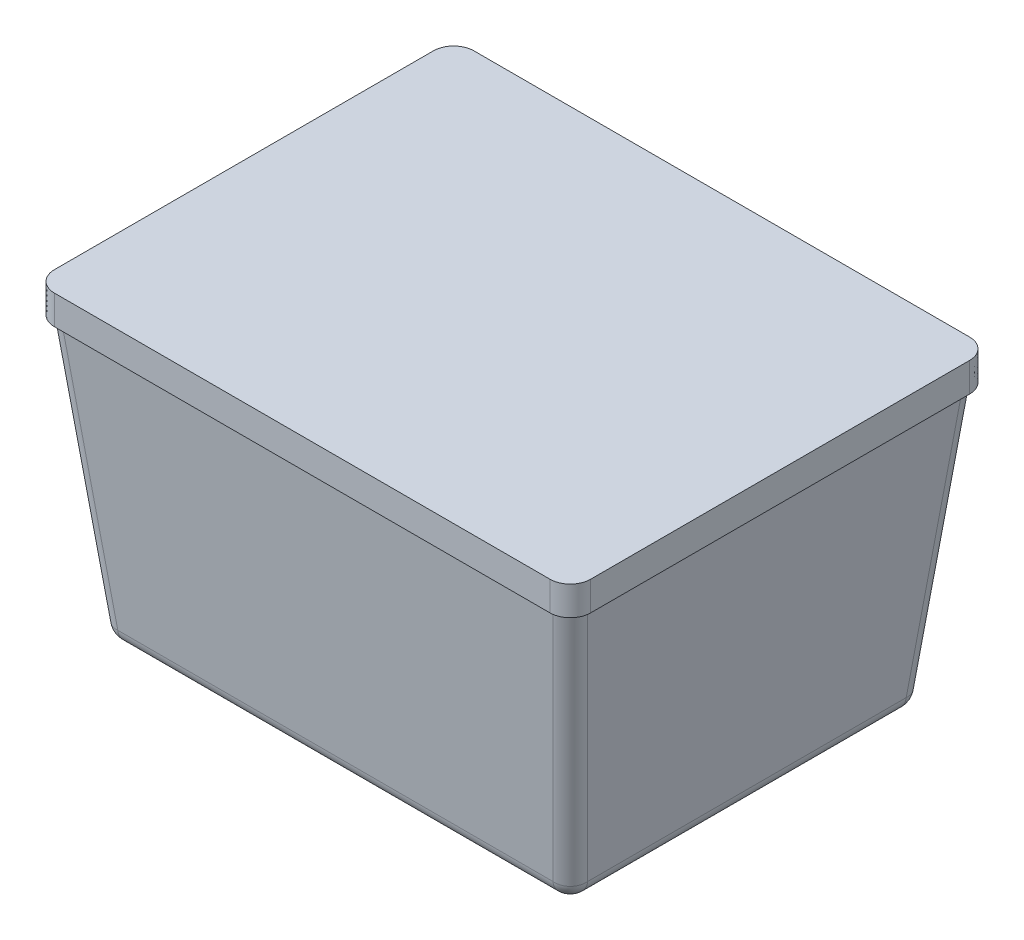
SolidWorks part; units mm, degrees
ref_plane "Alzado" through (0, 0, 0) normal (0, 0, 1) x (1, 0, 0)
ref_plane "Planta" through (0, 0, 0) normal (0, 1, 0) x (1, 0, 0)
ref_plane "Vista lateral" through (0, 0, 0) normal (1, 0, 0) x (0, 0, -1)
sketch "Croquis1" plane through (0, 0, 0) normal (0, 1, 0) x (1, 0, 0)
  line L1 (400, -300) -> (-400, -300)
  line L2 (400, -300) -> (400, 300)
  line L3 (400, 300) -> (-400, 300)
  line L4 (-400, -300) -> (-400, 300)
  line L5 (400, -300) -> (-400, 300) construction
  line L6 (400, 300) -> (-400, -300) construction
  point P0 (0, 0)
  dimension "D1" = 600
  dimension "D2" = 800
extrude "Extruir1" add sketch "Croquis1" along normal blind 520 draft 6 draft outward yes
fillet "Redondeo1" radius 30 8 edges at (0, 0, 300) (400, 0, 0) (0, 0, -300) (-400, 0, 0) (-427.3271, 260, -327.3271) (427.3271, 260, -327.3271) (427.3271, 260, 327.3271) (-427.3271, 260, 327.3271)
shell "Vaciado1" thickness 10
sketch "Croquis2" plane through (0, 520, 0) normal (0, 1, 0) x (1, 0, 0)
  line L24 (424.8185, 359.6542) -> (-424.8185, 359.6542)
  line L25 (459.6542, -324.8185) -> (459.6542, 324.8185)
  line L26 (-424.8185, -359.6542) -> (424.8185, -359.6542)
  line L27 (-459.6542, 324.8185) -> (-459.6542, -324.8185)
  line L28 (424.8185, 359.6542) -> (-424.8185, 359.6542)
  line L29 (459.6542, -324.8185) -> (459.6542, 324.8185)
  line L30 (-424.8185, -359.6542) -> (424.8185, -359.6542)
  line L31 (-459.6542, 324.8185) -> (-459.6542, -324.8185)
  spline S0 degree 3 poles (663.0928, -3479.8397) (-47.6648, -298.1304) (-303.9531, 384.1635) (-432.7137, 358.7732) (-433.8149, 358.5002) (-435.4515, 358.0079) (-435.9946, 357.83) (-437.0755, 357.446) (-437.6138, 357.2397) (-440.2615, 356.1489) (-442.2653, 355.0812) (-445.1032, 353.1931) (-446.0209, 352.5157) (-447.3539, 351.425) (-447.7906, 351.0493) (-448.6395, 350.2812) (-449.053, 349.888) (-451.067, 347.8765) (-452.5079, 346.1233) (-454.4118, 343.2761) (-455.0058, 342.2851) (-456.0832, 340.2672) (-456.5688, 339.238) (-457.8704, 336.0912) (-458.5327, 333.9145) (-496.2815, 144.0654) (1020.3325, -196.8187) (3414.6325, -624.2857) knots -7.056418 -7.056418 -7.056418 -7.056418 0.125 0.125 0.1875 0.1875 0.21875 0.21875 0.25 0.25 0.375 0.375 0.4375 0.4375 0.46875 0.46875 0.5 0.5 0.625 0.625 0.6875 0.6875 0.75 0.75 0.875 0.875 11.262721 11.262721 11.262721 11.262721 only from (-424.8185, 359.6542) to (-459.6542, 324.8185)
  spline S1 degree 3 poles (-3379.8397, -763.0928) (-198.1304, -52.3352) (484.1635, 203.9531) (458.7732, 332.7137) (458.5002, 333.8149) (458.0079, 335.4515) (457.83, 335.9946) (457.446, 337.0755) (457.2397, 337.6138) (456.1489, 340.2615) (455.0812, 342.2653) (453.1931, 345.1032) (452.5157, 346.0209) (451.425, 347.3539) (451.0493, 347.7906) (450.2812, 348.6395) (449.888, 349.053) (447.8765, 351.067) (446.1233, 352.5079) (443.2761, 354.4118) (442.2851, 355.0058) (440.2672, 356.0832) (439.238, 356.5688) (436.0912, 357.8704) (433.9145, 358.5327) (244.0654, 396.2815) (-96.8187, -1120.3325) (-524.2857, -3514.6325) knots -7.056418 -7.056418 -7.056418 -7.056418 0.125 0.125 0.1875 0.1875 0.21875 0.21875 0.25 0.25 0.375 0.375 0.4375 0.4375 0.46875 0.46875 0.5 0.5 0.625 0.625 0.6875 0.6875 0.75 0.75 0.875 0.875 11.262721 11.262721 11.262721 11.262721 only from (459.6542, 324.8185) to (424.8185, 359.6542)
  spline S2 degree 3 poles (-663.0928, 3479.8397) (47.6648, 298.1304) (303.9531, -384.1635) (432.7137, -358.7732) (433.8149, -358.5002) (435.4515, -358.0079) (435.9946, -357.83) (437.0755, -357.446) (437.6138, -357.2397) (440.2615, -356.1489) (442.2653, -355.0812) (445.1032, -353.1931) (446.0209, -352.5157) (447.3539, -351.425) (447.7906, -351.0493) (448.6395, -350.2812) (449.053, -349.888) (451.067, -347.8765) (452.5079, -346.1233) (454.4118, -343.2761) (455.0058, -342.2851) (456.0832, -340.2672) (456.5688, -339.238) (457.8704, -336.0912) (458.5327, -333.9145) (496.2815, -144.0654) (-1020.3325, 196.8187) (-3414.6325, 624.2857) knots -7.056418 -7.056418 -7.056418 -7.056418 0.125 0.125 0.1875 0.1875 0.21875 0.21875 0.25 0.25 0.375 0.375 0.4375 0.4375 0.46875 0.46875 0.5 0.5 0.625 0.625 0.6875 0.6875 0.75 0.75 0.875 0.875 11.262721 11.262721 11.262721 11.262721 only from (424.8185, -359.6542) to (459.6542, -324.8185)
  spline S3 degree 3 poles (3379.8397, 763.0928) (198.1304, 52.3352) (-484.1635, -203.9531) (-458.7732, -332.7137) (-458.5002, -333.8149) (-458.0079, -335.4515) (-457.83, -335.9946) (-457.446, -337.0755) (-457.2397, -337.6138) (-456.1489, -340.2615) (-455.0812, -342.2653) (-453.1931, -345.1032) (-452.5157, -346.0209) (-451.425, -347.3539) (-451.0493, -347.7906) (-450.2812, -348.6395) (-449.888, -349.053) (-447.8765, -351.067) (-446.1233, -352.5079) (-443.2761, -354.4118) (-442.2851, -355.0058) (-440.2672, -356.0832) (-439.238, -356.5688) (-436.0912, -357.8704) (-433.9145, -358.5327) (-244.0654, -396.2815) (96.8187, 1120.3325) (524.2857, 3514.6325) knots -7.056418 -7.056418 -7.056418 -7.056418 0.125 0.125 0.1875 0.1875 0.21875 0.21875 0.25 0.25 0.375 0.375 0.4375 0.4375 0.46875 0.46875 0.5 0.5 0.625 0.625 0.6875 0.6875 0.75 0.75 0.875 0.875 11.262721 11.262721 11.262721 11.262721 only from (-459.6542, -324.8185) to (-424.8185, -359.6542)
  spline S4 degree 3 poles (-424.8185, 359.6542) (-427.1201, 359.6542) (-429.3809, 359.4304) (-432.7137, 358.7732) (-433.8149, 358.5002) (-435.4515, 358.0079) (-435.9946, 357.83) (-437.0755, 357.446) (-437.6138, 357.2397) (-440.2615, 356.1489) (-442.2653, 355.0812) (-445.1032, 353.1931) (-446.0209, 352.5157) (-447.3539, 351.425) (-447.7906, 351.0493) (-448.6395, 350.2812) (-449.053, 349.888) (-451.067, 347.8765) (-452.5079, 346.1233) (-454.4118, 343.2761) (-455.0058, 342.2851) (-456.0832, 340.2672) (-456.5688, 339.238) (-457.8704, 336.0912) (-458.5327, 333.9145) (-459.4304, 329.3998) (-459.6542, 327.1202) (-459.6542, 324.8185) knots 0 0 0 0 0.125 0.125 0.1875 0.1875 0.21875 0.21875 0.25 0.25 0.375 0.375 0.4375 0.4375 0.46875 0.46875 0.5 0.5 0.625 0.625 0.6875 0.6875 0.75 0.75 0.875 0.875 1 1 1 1
  spline S5 degree 3 poles (459.6542, 324.8185) (459.6542, 327.1201) (459.4304, 329.3809) (458.7732, 332.7137) (458.5002, 333.8149) (458.0079, 335.4515) (457.83, 335.9946) (457.446, 337.0755) (457.2397, 337.6138) (456.1489, 340.2615) (455.0812, 342.2653) (453.1931, 345.1032) (452.5157, 346.0209) (451.425, 347.3539) (451.0493, 347.7906) (450.2812, 348.6395) (449.888, 349.053) (447.8765, 351.067) (446.1233, 352.5079) (443.2761, 354.4118) (442.2851, 355.0058) (440.2672, 356.0832) (439.238, 356.5688) (436.0912, 357.8704) (433.9145, 358.5327) (429.3998, 359.4304) (427.1202, 359.6542) (424.8185, 359.6542) knots 0 0 0 0 0.125 0.125 0.1875 0.1875 0.21875 0.21875 0.25 0.25 0.375 0.375 0.4375 0.4375 0.46875 0.46875 0.5 0.5 0.625 0.625 0.6875 0.6875 0.75 0.75 0.875 0.875 1 1 1 1
  spline S6 degree 3 poles (424.8185, -359.6542) (427.1201, -359.6542) (429.3809, -359.4304) (432.7137, -358.7732) (433.8149, -358.5002) (435.4515, -358.0079) (435.9946, -357.83) (437.0755, -357.446) (437.6138, -357.2397) (440.2615, -356.1489) (442.2653, -355.0812) (445.1032, -353.1931) (446.0209, -352.5157) (447.3539, -351.425) (447.7906, -351.0493) (448.6395, -350.2812) (449.053, -349.888) (451.067, -347.8765) (452.5079, -346.1233) (454.4118, -343.2761) (455.0058, -342.2851) (456.0832, -340.2672) (456.5688, -339.238) (457.8704, -336.0912) (458.5327, -333.9145) (459.4304, -329.3998) (459.6542, -327.1202) (459.6542, -324.8185) knots 0 0 0 0 0.125 0.125 0.1875 0.1875 0.21875 0.21875 0.25 0.25 0.375 0.375 0.4375 0.4375 0.46875 0.46875 0.5 0.5 0.625 0.625 0.6875 0.6875 0.75 0.75 0.875 0.875 1 1 1 1
  spline S7 degree 3 poles (-459.6542, -324.8185) (-459.6542, -327.1201) (-459.4304, -329.3809) (-458.7732, -332.7137) (-458.5002, -333.8149) (-458.0079, -335.4515) (-457.83, -335.9946) (-457.446, -337.0755) (-457.2397, -337.6138) (-456.1489, -340.2615) (-455.0812, -342.2653) (-453.1931, -345.1032) (-452.5157, -346.0209) (-451.425, -347.3539) (-451.0493, -347.7906) (-450.2812, -348.6395) (-449.888, -349.053) (-447.8765, -351.067) (-446.1233, -352.5079) (-443.2761, -354.4118) (-442.2851, -355.0058) (-440.2672, -356.0832) (-439.238, -356.5688) (-436.0912, -357.8704) (-433.9145, -358.5327) (-429.3998, -359.4304) (-427.1202, -359.6542) (-424.8185, -359.6542) knots 0 0 0 0 0.125 0.125 0.1875 0.1875 0.21875 0.21875 0.25 0.25 0.375 0.375 0.4375 0.4375 0.46875 0.46875 0.5 0.5 0.625 0.625 0.6875 0.6875 0.75 0.75 0.875 0.875 1 1 1 1
  dimension "D1" = 5
extrude "Extruir2" add sketch "Croquis2" against normal blind 40 separate body
sketch "Croquis3" plane through (0, 520, 0) normal (0, 1, 0) x (1, 0, 0)
  line L4 (-459.6542, 324.8185) -> (-459.6542, -324.8185)
  line L5 (-424.8185, -359.6542) -> (424.8185, -359.6542)
  line L6 (459.6542, -324.8185) -> (459.6542, 324.8185)
  line L7 (424.8185, 359.6542) -> (-424.8185, 359.6542)
  line L8 (-459.6542, 324.8185) -> (-459.6542, -324.8185)
  line L9 (-424.8185, -359.6542) -> (424.8185, -359.6542)
  line L10 (459.6542, -324.8185) -> (459.6542, 324.8185)
  line L11 (424.8185, 359.6542) -> (-424.8185, 359.6542)
  spline S4 degree 3 poles (663.0928, -3479.8397) (-47.6648, -298.1304) (-303.9531, 384.1635) (-432.7137, 358.7732) (-433.8149, 358.5002) (-435.4515, 358.0079) (-435.9946, 357.83) (-437.0755, 357.446) (-437.6138, 357.2397) (-440.2615, 356.1489) (-442.2653, 355.0812) (-445.1032, 353.1931) (-446.0209, 352.5157) (-447.3539, 351.425) (-447.7906, 351.0493) (-448.6395, 350.2812) (-449.053, 349.888) (-451.067, 347.8765) (-452.5079, 346.1233) (-454.4118, 343.2761) (-455.0058, 342.2851) (-456.0832, 340.2672) (-456.5688, 339.238) (-457.8704, 336.0912) (-458.5327, 333.9145) (-496.2815, 144.0654) (1020.3325, -196.8187) (3414.6325, -624.2857) knots -7.056418 -7.056418 -7.056418 -7.056418 0.125 0.125 0.1875 0.1875 0.21875 0.21875 0.25 0.25 0.375 0.375 0.4375 0.4375 0.46875 0.46875 0.5 0.5 0.625 0.625 0.6875 0.6875 0.75 0.75 0.875 0.875 11.262721 11.262721 11.262721 11.262721 only from (-424.8185, 359.6542) to (-459.6542, 324.8185)
  spline S5 degree 3 poles (3379.8397, 763.0928) (198.1304, 52.3352) (-484.1635, -203.9531) (-458.7732, -332.7137) (-458.5002, -333.8149) (-458.0079, -335.4515) (-457.83, -335.9946) (-457.446, -337.0755) (-457.2397, -337.6138) (-456.1489, -340.2615) (-455.0812, -342.2653) (-453.1931, -345.1032) (-452.5157, -346.0209) (-451.425, -347.3539) (-451.0493, -347.7906) (-450.2812, -348.6395) (-449.888, -349.053) (-447.8765, -351.067) (-446.1233, -352.5079) (-443.2761, -354.4118) (-442.2851, -355.0058) (-440.2672, -356.0832) (-439.238, -356.5688) (-436.0912, -357.8704) (-433.9145, -358.5327) (-244.0654, -396.2815) (96.8187, 1120.3325) (524.2857, 3514.6325) knots -7.056418 -7.056418 -7.056418 -7.056418 0.125 0.125 0.1875 0.1875 0.21875 0.21875 0.25 0.25 0.375 0.375 0.4375 0.4375 0.46875 0.46875 0.5 0.5 0.625 0.625 0.6875 0.6875 0.75 0.75 0.875 0.875 11.262721 11.262721 11.262721 11.262721 only from (-459.6542, -324.8185) to (-424.8185, -359.6542)
  spline S6 degree 3 poles (-663.0928, 3479.8397) (47.6648, 298.1304) (303.9531, -384.1635) (432.7137, -358.7732) (433.8149, -358.5002) (435.4515, -358.0079) (435.9946, -357.83) (437.0755, -357.446) (437.6138, -357.2397) (440.2615, -356.1489) (442.2653, -355.0812) (445.1032, -353.1931) (446.0209, -352.5157) (447.3539, -351.425) (447.7906, -351.0493) (448.6395, -350.2812) (449.053, -349.888) (451.067, -347.8765) (452.5079, -346.1233) (454.4118, -343.2761) (455.0058, -342.2851) (456.0832, -340.2672) (456.5688, -339.238) (457.8704, -336.0912) (458.5327, -333.9145) (496.2815, -144.0654) (-1020.3325, 196.8187) (-3414.6325, 624.2857) knots -7.056418 -7.056418 -7.056418 -7.056418 0.125 0.125 0.1875 0.1875 0.21875 0.21875 0.25 0.25 0.375 0.375 0.4375 0.4375 0.46875 0.46875 0.5 0.5 0.625 0.625 0.6875 0.6875 0.75 0.75 0.875 0.875 11.262721 11.262721 11.262721 11.262721 only from (424.8185, -359.6542) to (459.6542, -324.8185)
  spline S7 degree 3 poles (-3379.8397, -763.0928) (-198.1304, -52.3352) (484.1635, 203.9531) (458.7732, 332.7137) (458.5002, 333.8149) (458.0079, 335.4515) (457.83, 335.9946) (457.446, 337.0755) (457.2397, 337.6138) (456.1489, 340.2615) (455.0812, 342.2653) (453.1931, 345.1032) (452.5157, 346.0209) (451.425, 347.3539) (451.0493, 347.7906) (450.2812, 348.6395) (449.888, 349.053) (447.8765, 351.067) (446.1233, 352.5079) (443.2761, 354.4118) (442.2851, 355.0058) (440.2672, 356.0832) (439.238, 356.5688) (436.0912, 357.8704) (433.9145, 358.5327) (244.0654, 396.2815) (-96.8187, -1120.3325) (-524.2857, -3514.6325) knots -7.056418 -7.056418 -7.056418 -7.056418 0.125 0.125 0.1875 0.1875 0.21875 0.21875 0.25 0.25 0.375 0.375 0.4375 0.4375 0.46875 0.46875 0.5 0.5 0.625 0.625 0.6875 0.6875 0.75 0.75 0.875 0.875 11.262721 11.262721 11.262721 11.262721 only from (459.6542, 324.8185) to (424.8185, 359.6542)
  spline S8 degree 3 poles (-424.8185, 359.6542) (-427.1201, 359.6542) (-429.3809, 359.4304) (-432.7137, 358.7732) (-433.8149, 358.5002) (-435.4515, 358.0079) (-435.9946, 357.83) (-437.0755, 357.446) (-437.6138, 357.2397) (-440.2615, 356.1489) (-442.2653, 355.0812) (-445.1032, 353.1931) (-446.0209, 352.5157) (-447.3539, 351.425) (-447.7906, 351.0493) (-448.6395, 350.2812) (-449.053, 349.888) (-451.067, 347.8765) (-452.5079, 346.1233) (-454.4118, 343.2761) (-455.0058, 342.2851) (-456.0832, 340.2672) (-456.5688, 339.238) (-457.8704, 336.0912) (-458.5327, 333.9145) (-459.4304, 329.3998) (-459.6542, 327.1202) (-459.6542, 324.8185) knots 0 0 0 0 0.125 0.125 0.1875 0.1875 0.21875 0.21875 0.25 0.25 0.375 0.375 0.4375 0.4375 0.46875 0.46875 0.5 0.5 0.625 0.625 0.6875 0.6875 0.75 0.75 0.875 0.875 1 1 1 1
  spline S9 degree 3 poles (-459.6542, -324.8185) (-459.6542, -327.1201) (-459.4304, -329.3809) (-458.7732, -332.7137) (-458.5002, -333.8149) (-458.0079, -335.4515) (-457.83, -335.9946) (-457.446, -337.0755) (-457.2397, -337.6138) (-456.1489, -340.2615) (-455.0812, -342.2653) (-453.1931, -345.1032) (-452.5157, -346.0209) (-451.425, -347.3539) (-451.0493, -347.7906) (-450.2812, -348.6395) (-449.888, -349.053) (-447.8765, -351.067) (-446.1233, -352.5079) (-443.2761, -354.4118) (-442.2851, -355.0058) (-440.2672, -356.0832) (-439.238, -356.5688) (-436.0912, -357.8704) (-433.9145, -358.5327) (-429.3998, -359.4304) (-427.1202, -359.6542) (-424.8185, -359.6542) knots 0 0 0 0 0.125 0.125 0.1875 0.1875 0.21875 0.21875 0.25 0.25 0.375 0.375 0.4375 0.4375 0.46875 0.46875 0.5 0.5 0.625 0.625 0.6875 0.6875 0.75 0.75 0.875 0.875 1 1 1 1
  spline S10 degree 3 poles (424.8185, -359.6542) (427.1201, -359.6542) (429.3809, -359.4304) (432.7137, -358.7732) (433.8149, -358.5002) (435.4515, -358.0079) (435.9946, -357.83) (437.0755, -357.446) (437.6138, -357.2397) (440.2615, -356.1489) (442.2653, -355.0812) (445.1032, -353.1931) (446.0209, -352.5157) (447.3539, -351.425) (447.7906, -351.0493) (448.6395, -350.2812) (449.053, -349.888) (451.067, -347.8765) (452.5079, -346.1233) (454.4118, -343.2761) (455.0058, -342.2851) (456.0832, -340.2672) (456.5688, -339.238) (457.8704, -336.0912) (458.5327, -333.9145) (459.4304, -329.3998) (459.6542, -327.1202) (459.6542, -324.8185) knots 0 0 0 0 0.125 0.125 0.1875 0.1875 0.21875 0.21875 0.25 0.25 0.375 0.375 0.4375 0.4375 0.46875 0.46875 0.5 0.5 0.625 0.625 0.6875 0.6875 0.75 0.75 0.875 0.875 1 1 1 1
  spline S11 degree 3 poles (459.6542, 324.8185) (459.6542, 327.1201) (459.4304, 329.3809) (458.7732, 332.7137) (458.5002, 333.8149) (458.0079, 335.4515) (457.83, 335.9946) (457.446, 337.0755) (457.2397, 337.6138) (456.1489, 340.2615) (455.0812, 342.2653) (453.1931, 345.1032) (452.5157, 346.0209) (451.425, 347.3539) (451.0493, 347.7906) (450.2812, 348.6395) (449.888, 349.053) (447.8765, 351.067) (446.1233, 352.5079) (443.2761, 354.4118) (442.2851, 355.0058) (440.2672, 356.0832) (439.238, 356.5688) (436.0912, 357.8704) (433.9145, 358.5327) (429.3998, 359.4304) (427.1202, 359.6542) (424.8185, 359.6542) knots 0 0 0 0 0.125 0.125 0.1875 0.1875 0.21875 0.21875 0.25 0.25 0.375 0.375 0.4375 0.4375 0.46875 0.46875 0.5 0.5 0.625 0.625 0.6875 0.6875 0.75 0.75 0.875 0.875 1 1 1 1
  dimension "D1" = 0
extrude "Extruir3" add sketch "Croquis3" along normal blind 10
